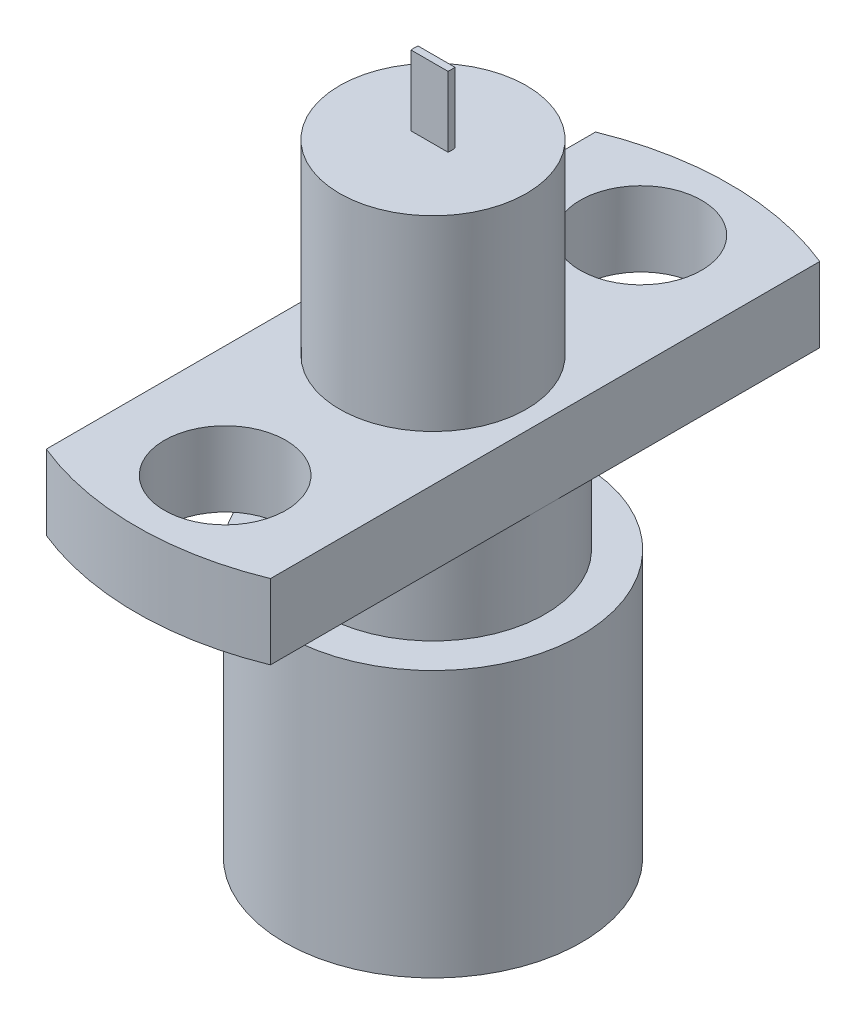
SolidWorks part; units mm, degrees
material "AISI 316 Stainless Steel Sheet (SS)"
ref_plane "Front Plane" through (0, 0, 0) normal (0, 0, 1) x (1, 0, 0)
ref_plane "Top Plane" through (0, 0, 0) normal (0, 1, 0) x (1, 0, 0)
ref_plane "Right Plane" through (0, 0, 0) normal (1, 0, 0) x (0, 0, -1)
sketch "Sketch1" plane through (0, 0, 0) normal (0, 1, 0) x (1, 0, 0)
  line L0 (-1000, 0) -> (49000, 0) construction
  line L1 (0, -1000) -> (0, 49000) construction
  line L2 (-2.4, 5.879) -> (-2.4, -5.879)
  line L3 (2.4, 5.879) -> (2.4, -5.879)
  circle A0 centre (0, 0) radius 6.35 construction
  arc A1 (-2.4, 5.879) -> (2.4, 5.879) centre (0, 0) cw
  arc A2 (-2.4, -5.879) -> (2.4, -5.879) centre (0, 0) ccw
  dimension "D1" = 12.7
  dimension "D2" = 4.8
extrude "Boss-Extrude1" add sketch "Sketch1" along normal blind 1.6
sketch "Sketch2" plane through (0, 1.6, 0) normal (0, 1, 0) x (1, 0, 0)
  line L0 (-1000, 0) -> (49000, 0) construction
  line L1 (0, -1000) -> (0, 49000) construction
  circle A0 centre (0, 4.45) radius 1.3
  circle A1 centre (0, -4.45) radius 1.3
  dimension "D1" = 2.6
  dimension "D2" = 8.9
extrude "Cut-Extrude1" cut sketch "Sketch2" against normal up to surface (1.6 mm away) up to face at (0, 0, 0)
sketch "Sketch3" plane through (0, 1.6, 0) normal (0, 1, 0) x (1, 0, 0)
  circle A0 centre (0, 0) radius 2
  dimension "D1" = 4
extrude "Boss-Extrude2" add sketch "Sketch3" along normal blind 4
sketch "Sketch4" plane through (0, 5.6, 0) normal (0, 1, 0) x (1, 0, 0)
  line L0 (-1000, 0) -> (49000, 0) construction
  line L1 (0, -1000) -> (0, 49000) construction
  line L2 (0.3929, 0.075) -> (-0.3929, 0.075)
  line L3 (0.3929, -0.075) -> (-0.3929, -0.075)
  circle A0 centre (0, 0) radius 0.4 construction
  arc A1 (0.3929, 0.075) -> (0.3929, -0.075) centre (0, 0) cw
  arc A2 (-0.3929, 0.075) -> (-0.3929, -0.075) centre (0, 0) ccw
  dimension "D1" = 0.8
  dimension "D2" = 0.15
extrude "Boss-Extrude3" add sketch "Sketch4" along normal blind 1.5
sketch "Sketch5" plane through (0, 0, 0) normal (0, -1, 0) x (1, 0, 0)
  circle A0 centre (0, 0) radius 2.4
  dimension "D1" = 4.8
extrude "Boss-Extrude5" add sketch "Sketch5" along normal blind 2
sketch "Sketch6" plane through (0, -2, 0) normal (0, -1, 0) x (1, 0, 0)
  circle A0 centre (0, 0) radius 3.175
  circle A1 centre (0, 0) radius 2.4 construction
  dimension "D1" = 6.35
extrude "Boss-Extrude7" add sketch "Sketch6" along normal offset from surface (5.7 mm away) 9.3 up to face at (0, 1.6, -2)
